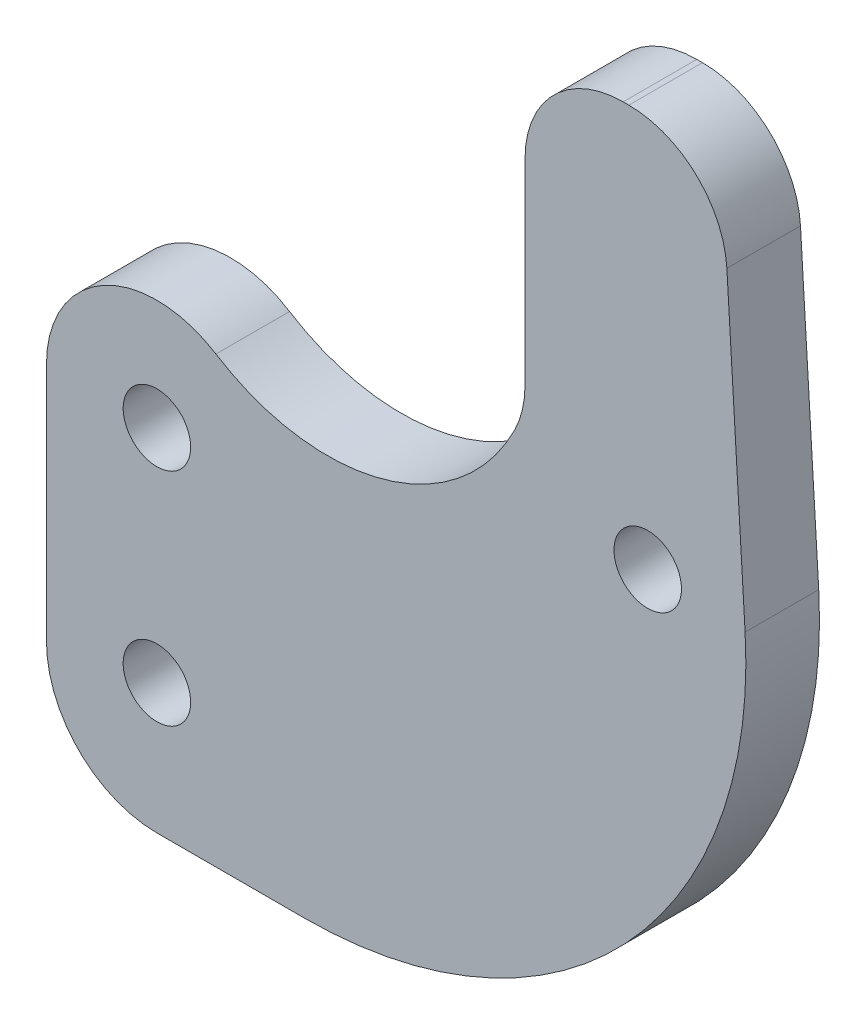
SolidWorks part; units mm, degrees
ref_plane "Front Plane" through (0, 0, 0) normal (0, 0, 1) x (1, 0, 0)
ref_plane "Top Plane" through (0, 0, 0) normal (0, 1, 0) x (1, 0, 0)
ref_plane "Right Plane" through (0, 0, 0) normal (1, 0, 0) x (0, 0, -1)
sketch "Sketch1" plane through (0, 0, 0) normal (0, 0, 1) x (1, 0, 0)
  line L0 (-4.5, -0.8) -> (-4.5, 9)
  line L1 (20, 14) -> (20, 30) construction
  line L2 (15, 18) -> (15, 30)
  line L3 (15, 30) -> (23, 30)
  line L4 (23.9681, 13.7718) -> (23, 30)
  line L5 (3.1177, 0) -> (1.5588, 2.7) construction
  line L6 (0, -5.3) -> (6, -5.3)
  line L7 (1.5588, 2.7) -> (-1.5588, 2.7) construction
  line L8 (-1.5588, 2.7) -> (-3.1177, 0) construction
  line L9 (-3.1177, 0) -> (-1.5588, -2.7) construction
  line L10 (-1.5588, -2.7) -> (1.5588, -2.7) construction
  line L11 (1.5588, -2.7) -> (3.1177, 0) construction
  circle A0 centre (0, 0) radius 1.375
  circle A1 centre (0, 9) radius 1.375
  arc A3 (2.4045, 12.8037) -> (-4.5, 9) centre (0, 9) ccw
  arc A4 (15, 18) -> (14.5859, 16.2276) centre (11, 18) cw
  arc A5 (6, -5.3) -> (23.9681, 13.7718) centre (6, 12.7) ccw
  circle A6 centre (0, 0) radius 2.7 construction
  arc A7 (2.4045, 12.8037) -> (14.5859, 16.2276) centre (6.9537, 20) ccw
  circle A8 centre (20, 14) radius 1.375
  circle A9 centre (0, 9) radius 14.3 construction
  arc A10 (-4.5, -0.8) -> (0, -5.3) centre (0, -0.8) ccw
  dimension "D2" = 2.75
  dimension "D3" = 2.75
  dimension "D4" = 9
  dimension "D6" = 4
  dimension "D9" = 5.4
  dimension "D14" = 9
  dimension "D15" = 18
  dimension "D16" = 2.75
  dimension "D17" = 28.6
  dimension "D1" = 9
  dimension "D5" = 15
  dimension "D7" = 30
  dimension "D8" = 8
  dimension "D10" = 12
  dimension "D11" = 10
  dimension "D12" = 3
  dimension "D13" = 16
extrude "Boss-Extrude1" add sketch "Sketch1" along normal blind 3
fillet "Fillet1" radius 4 2 edges at (15, 30, 1.5) (23, 30, 1.5)
sketch "Sketch2" plane through (0, 0, 0) normal (0, 0, 1) x (1, 0, 0)
  point P0 (0, 9)
  point P1 (20, 14)
  point P3 (0, 0)
